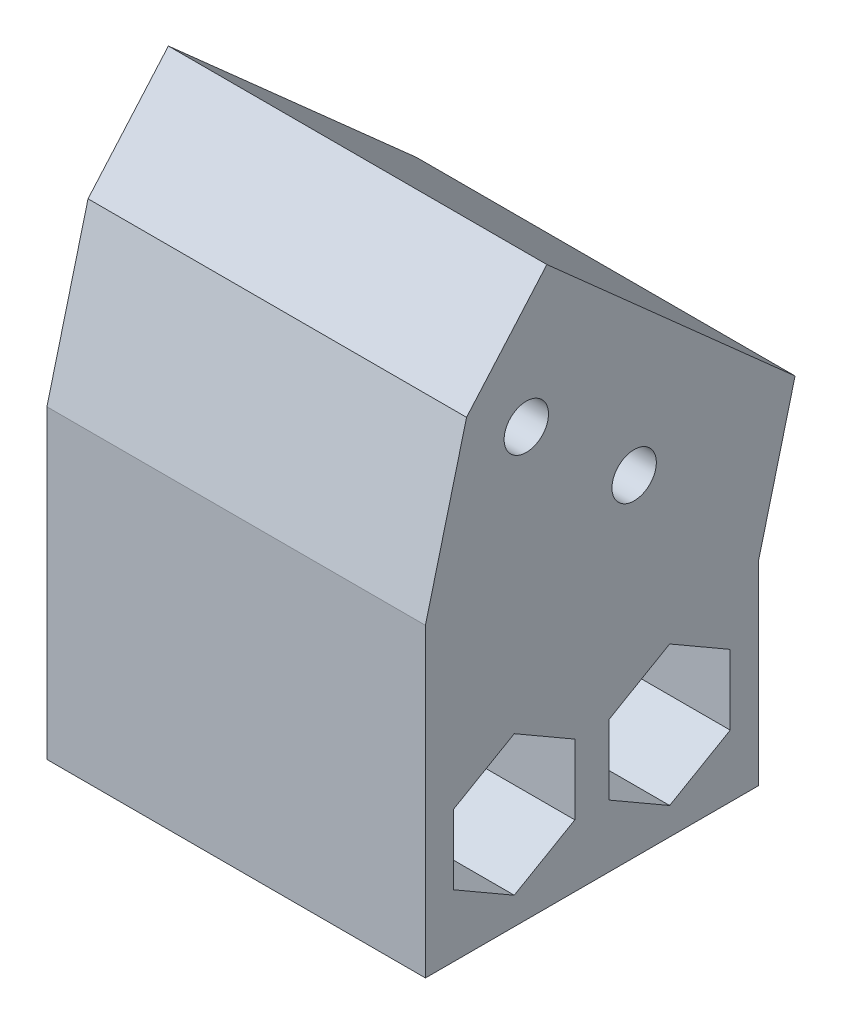
SolidWorks part; units mm, degrees
ref_plane "Front Plane" through (0, 0, 0) normal (0, 0, 1) x (1, 0, 0)
ref_plane "Top Plane" through (0, 0, 0) normal (0, 1, 0) x (1, 0, 0)
ref_plane "Right Plane" through (0, 0, 0) normal (1, 0, 0) x (0, 0, -1)
sketch "Sketch1" plane through (0, 0, 0) normal (1, 0, 0) x (0, 0, -1)
  line L0 (-7.5, 0) -> (7.5, 0)
  line L1 (-7.5, 0) -> (-7.5, 15.76)
  line L2 (7.5, 0) -> (7.5, 10.76)
  line L3 (-7.5, 15.76) -> (-4.1038, 28.9395)
  line L4 (7.5, 10.76) -> (9.1494, 17.1609)
  line L5 (-4.1038, 28.9395) -> (9.1494, 17.1609)
  line L6 (7.7469, 11.7181) -> (-5.5064, 23.4967) construction
  circle A0 centre (-2.9575, 21.2314) radius 1
  circle A1 centre (1.9011, 16.9135) radius 1
  point P4 (0, 0)
  dimension "D7" = 5
  dimension "D8" = 2
  dimension "D9" = 2
  dimension "D10" = 6.5
  dimension "D11" = 3.41
  dimension "D1" = 15
  dimension "D2" = 15.76
  dimension "D3" = 10.76
  dimension "D4" = 194.45
  dimension "D5" = 6.61
  dimension "D6" = 13.61
extrude "Boss-Extrude1" add sketch "Sketch1" along normal blind 17.05
chamfer "Chamfer3" distance 2 angle 45 2 edges at (17.05, 0, 0) (8.525, 0, 7.5)
sketch "Sketch4" plane through (17.05, 0, 0) normal (1, 0, 0) x (0, 0, -1)
  circle A0 centre (-3.5, 6.38) radius 1.411
  circle A1 centre (3.5, 6.38) radius 1.411
  point P6 (0, 0)
  point P7 (0, 0)
  point P8 (0, 0)
extrude "Cut-Extrude2" cut sketch "Sketch4" against normal through all
sketch "Sketch5" plane through (17.05, 0, 0) normal (1, 0, 0) x (0, 0, -1)
  line L0 (-4.1038, 28.9395) -> (-2.0302, 27.0965)
  line L1 (9.1494, 17.1609) -> (-4.1038, 28.9395) construction
  line L2 (-2.0302, 27.0965) -> (-5.6484, 22.9455)
  line L3 (-4.1038, 28.9395) -> (-7.5, 15.76) construction
  line L4 (-6.1092, 22.427) -> (-4.4484, 24.2957) construction
  line L5 (-5.6484, 22.9455) -> (-4.1038, 28.9395)
extrude "Cut-Extrude3" cut sketch "Sketch5" against normal through all contours L5 L0 L2
sketch "Sketch6" plane through (17.05, 0, 0) normal (1, 0, 0) x (0, 0, -1)
  line L0 (0, 6.38) -> (0, 4.0239) construction
  line L1 (-3.5, 3.23) -> (-0.772, 4.805)
  line L2 (-0.772, 4.805) -> (-0.772, 7.955)
  line L3 (-0.772, 7.955) -> (-3.5, 9.53)
  line L4 (-3.5, 9.53) -> (-6.228, 7.955)
  line L5 (-6.228, 7.955) -> (-6.228, 4.805)
  line L6 (-6.228, 4.805) -> (-3.5, 3.23)
  line L7 (6.228, 4.805) -> (3.5, 3.23)
  line L8 (6.228, 7.955) -> (6.228, 4.805)
  line L9 (3.5, 9.53) -> (6.228, 7.955)
  line L10 (0.772, 7.955) -> (3.5, 9.53)
  line L11 (0.772, 4.805) -> (0.772, 7.955)
  line L12 (3.5, 3.23) -> (0.772, 4.805)
  circle A0 centre (-3.5, 6.38) radius 2.728 construction
  point P19 (0, 0)
  point P20 (0, 0)
  point P21 (0, 0)
  dimension "D1" = 6.3
extrude "Cut-Extrude4" cut sketch "Sketch6" against normal blind 10
